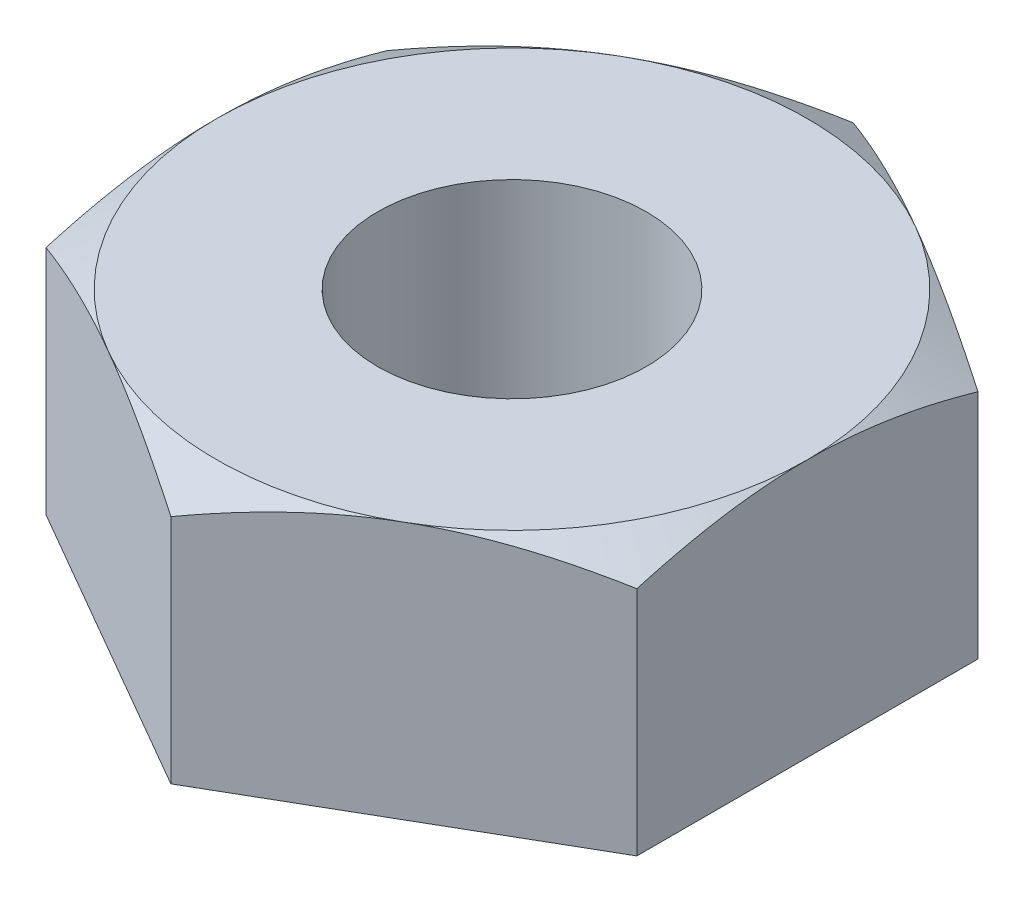
SolidWorks part; units mm, degrees
ref_plane "Front Plane" through (0, 0, 0) normal (0, 0, 1) x (1, 0, 0)
ref_plane "Top Plane" through (0, 0, 0) normal (0, 1, 0) x (1, 0, 0)
ref_plane "Right Plane" through (0, 0, 0) normal (1, 0, 0) x (0, 0, -1)
sketch "Sketch1" plane through (0, 0, 0) normal (0, 1, 0) x (1, 0, 0)
  line L1 (0, 3.1754) -> (-2.75, 1.5877)
  line L2 (-2.75, 1.5877) -> (-2.75, -1.5877)
  line L3 (-2.75, -1.5877) -> (0, -3.1754)
  line L4 (0, -3.1754) -> (2.75, -1.5877)
  line L5 (2.75, -1.5877) -> (2.75, 1.5877)
  line L6 (2.75, 1.5877) -> (0, 3.1754)
  circle A0 centre (0, 0) radius 2.75 construction
  dimension "NT_S" = 5.5
extrude "Boss-Extrude1" add sketch "Sketch1" against normal blind 2.4
sketch "Sketch2" plane through (0, 0, 0) normal (1, 0, 0) x (0, 0, -1)
  line L0 (0, 0) -> (0, -2.4) construction
  line L1 (-1.5877, -2.4) -> (1.5877, -2.4) construction
  line L2 (2.75, 0) -> (3.1754, 0)
  line L3 (3.1754, 0) -> (3.1754, -0.2456)
  line L4 (3.1754, -0.2456) -> (2.75, 0)
  line L5 (1.5877, 0) -> (3.1754, 0) construction
  line L6 (3.1754, -2.4) -> (3.1754, 0) construction
  dimension "D1" = 30
revolve "Cut-Revolve1" cut sketch "Sketch2" angle 360 about L0
hole_wizard "Tapped Hole1" positions "Sketch4" profile "Sketch3" tap size "M5x0.8" standard "JIS" end condition through all
sketch "Sketch4" plane through (0, 0, 0) normal (0, 1, 0) x (1, 0, 0)
  point P0 (0, 0)
sketch "Sketch3" plane through (0, 0, 0) normal (1, 0, 0) x (0, 0, 1)
  line L0 (0, 0) -> (0, 2.4)
  line L1 (0, 2.4) -> (1.25, 2.4)
  line L2 (1.25, 2.4) -> (1.25, 0)
  line L5 (1.25, 0) -> (0, 0)
  line L11 (0, 0) -> (0, 2.4) construction
  dimension "Thru Tap Drill Dia." = 2.5
  dimension "Thru Tap Drill Depth" = 2.4
cosmetic thread "Hole Thread1" parameters "NT_M"=3
